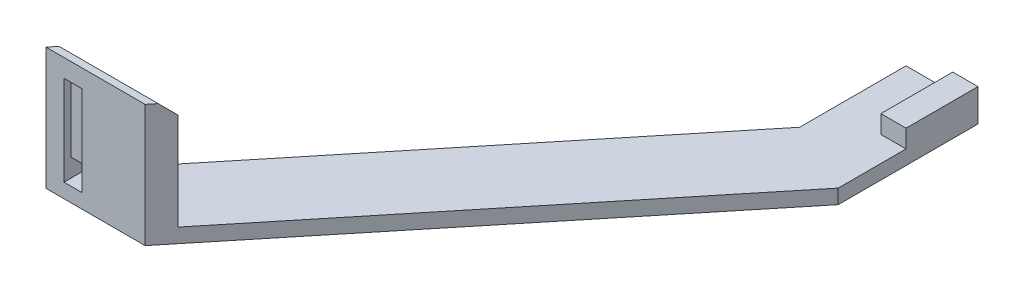
SolidWorks part; units mm, degrees
ref_plane "Front Plane" through (0, 0, 0) normal (0, 0, 1) x (1, 0, 0)
ref_plane "Top Plane" through (0, 0, 0) normal (0, 1, 0) x (1, 0, 0)
ref_plane "Right Plane" through (0, 0, 0) normal (1, 0, 0) x (0, 0, -1)
sketch "Sketch1" plane through (0, 0, 0) normal (0, 1, 0) x (1, 0, 0)
  line L0 (-114, 0) -> (-86.4463, 0)
  line L1 (-114, 0) -> (-20, 115.4386)
  line L2 (0, 140) -> (0, 106.16)
  line L3 (-86.4463, 0) -> (0, 106.16)
  line L4 (-20, 145) -> (0, 145)
  line L5 (0, 145) -> (0, 140)
  line L6 (-20, 145) -> (-20, 115.4386)
  dimension "D2" = 50.845
  dimension "D3" = 129.156
  dimension "D4" = 114
  dimension "D5" = 20
  dimension "D6" = 5
  dimension "D7" = 140.845
  dimension "D10" = 140.844
extrude "Boss-Extrude1" add sketch "Sketch1" along normal blind 4
sketch "Sketch4" plane through (0, 4, 0) normal (0, 1, 0) x (1, 0, 0)
  line L1 (0, 145) -> (-7, 145)
  line L2 (0, 145) -> (0, 125)
  line L3 (0, 125) -> (-7, 125)
  line L4 (-7, 145) -> (-7, 125)
  dimension "D1" = 7
  dimension "D2" = 20
extrude "Boss-Extrude3" add sketch "Sketch4" along normal blind 5
sketch "Sketch5" plane through (0, 4, 0) normal (0, 1, 0) x (1, 0, 0)
  line L0 (-86.4463, 0) -> (-104, 0)
  line L1 (-86.4463, 0) -> (-82.3748, 5)
  line L2 (-86.4463, 0) -> (0, 106.16) construction
  line L3 (-82.3748, 5) -> (-109.9286, 5)
  line L4 (-20, 115.4386) -> (-114, 0) construction
  line L5 (-109.9286, 5) -> (-114, 0)
  line L6 (-109, 0) -> (-109, 2)
  line L7 (-109, 2) -> (-104, 2)
  line L8 (-104, 2) -> (-104, 0)
  line L9 (-109, 0) -> (-114, 0)
  dimension "D2" = 5
  dimension "D3" = 5
  dimension "D4" = 2
extrude "Boss-Extrude4" add sketch "Sketch5" along normal blind 30
sketch "Sketch6" plane through (0, 0, -2) normal (0, 0, 1) x (1, 0, 0)
  line L1 (-109, 4) -> (-104, 4)
  line L2 (-109, 4) -> (-109, 9)
  line L3 (-109, 9) -> (-104, 9)
  line L4 (-104, 4) -> (-104, 9)
  dimension "D1" = 5
  dimension "D2" = 5
extrude "Cut-Extrude2" cut sketch "Sketch6" against normal blind 30
sketch "Sketch7" plane through (0, 0, -2) normal (0, 0, 1) x (1, 0, 0)
  line L1 (-104, 34) -> (-109, 34)
  line L2 (-104, 34) -> (-104, 29)
  line L3 (-104, 29) -> (-109, 29)
  line L4 (-109, 34) -> (-109, 29)
  dimension "D1" = 5
  dimension "D2" = 5
extrude "Boss-Extrude5" add sketch "Sketch7" along normal blind 2
chamfer "Chamfer1" distance 3 angle 45 1 edges at (-96.1517, 34, -5)
